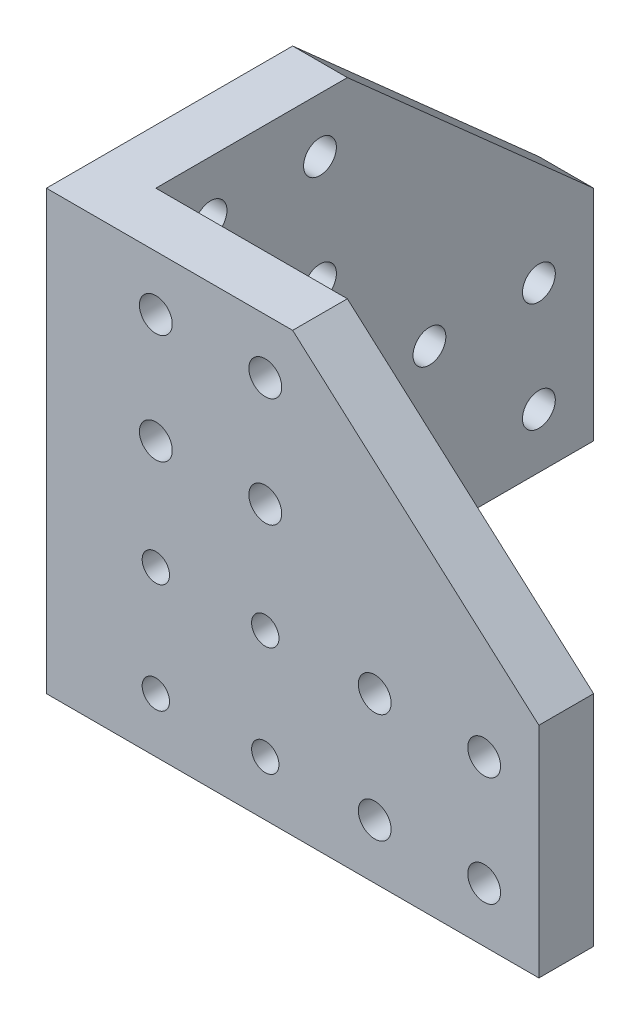
SolidWorks part; units mm, degrees
ref_plane "Front Plane" through (0, 0, 0) normal (0, 0, 1) x (1, 0, 0)
ref_plane "Top Plane" through (0, 0, 0) normal (0, 1, 0) x (1, 0, 0)
ref_plane "Right Plane" through (0, 0, 0) normal (1, 0, 0) x (0, 0, -1)
sketch "Sketch1" plane through (0, 0, 0) normal (0, 1, 0) x (1, 0, 0)
  line L0 (0, 0) -> (90, 0)
  line L1 (90, 0) -> (90, 10)
  line L2 (90, 10) -> (10, 10)
  line L3 (10, 10) -> (10, 90)
  line L4 (10, 90) -> (0, 90)
  line L5 (0, 90) -> (0, 0)
  dimension "D1" = 90
  dimension "D2" = 10
  dimension "D3" = 80
  dimension "D4" = 10
extrude "Boss-Extrude1" add sketch "Sketch1" along normal blind 80
sketch "Sketch2" plane through (0, 0, 0) normal (0, 0, 1) x (1, 0, 0)
  line L0 (90, 80) -> (90, 40)
  line L1 (90, 80) -> (90, 0) construction
  line L2 (90, 40) -> (45, 80)
  line L3 (0, 80) -> (90, 80) construction
  line L4 (45, 80) -> (90, 80)
extrude "Cut-Extrude1" cut sketch "Sketch2" against normal up to next
sketch "Sketch3" plane through (0, 0, 0) normal (-1, 0, 0) x (0, 0, 1)
  line L0 (-45, 80) -> (-90, 40)
  line L1 (-90, 80) -> (0, 80) construction
  line L2 (-90, 80) -> (-90, 0) construction
  line L3 (-90, 40) -> (-90, 80)
  line L4 (-90, 80) -> (-45, 80)
extrude "Cut-Extrude2" cut sketch "Sketch3" against normal up to next
sketch "Sketch4" plane through (0, 0, 0) normal (0, 0, 1) x (1, 0, 0)
  line L0 (0, 80) -> (0, 0) construction
  line L1 (90, 40) -> (90, 0) construction
  line L2 (0, 80) -> (45, 80) construction
  line L3 (0, 0) -> (90, 0) construction
  circle A0 centre (20, 30) radius 2.5
  circle A1 centre (40, 30) radius 2.5
  circle A2 centre (20, 10) radius 2.5
  circle A3 centre (40, 10) radius 2.5
  circle A4 centre (60, 10) radius 3
  circle A5 centre (80, 10) radius 3
  circle A6 centre (60, 30) radius 3
  circle A7 centre (80, 30) radius 3
  circle A8 centre (40, 50) radius 3
  circle A9 centre (20, 50) radius 3
  circle A10 centre (20, 70) radius 3
  circle A11 centre (40, 70) radius 3
  dimension "D8" = 6
  dimension "D9" = 5
  dimension "D1" = 20
  dimension "D2" = 20
  dimension "D3" = 10
  dimension "D4" = 20
  dimension "D5" = 20
  dimension "D6" = 20
  dimension "D7" = 10
  dimension "D10" = 10
extrude "Cut-Extrude3" cut sketch "Sketch4" against normal up to next
sketch "Sketch5" plane through (0, 0, 0) normal (-1, 0, 0) x (0, 0, 1)
  line L0 (0, 80) -> (0, 0) construction
  line L1 (-90, 40) -> (-90, 0) construction
  line L2 (-90, 0) -> (0, 0) construction
  line L3 (-45, 80) -> (0, 80) construction
  circle A0 centre (-20, 70) radius 3
  circle A1 centre (-40, 70) radius 3
  circle A2 centre (-20, 50) radius 3
  circle A3 centre (-40, 50) radius 3
  circle A4 centre (-20, 30) radius 3
  circle A5 centre (-40, 30) radius 3
  circle A6 centre (-20, 10) radius 3
  circle A7 centre (-40, 10) radius 3
  circle A8 centre (-60, 10) radius 3
  circle A9 centre (-60, 30) radius 3
  circle A10 centre (-80, 30) radius 3
  circle A11 centre (-80, 10) radius 3
  dimension "D1" = 6
  dimension "D2" = 20
  dimension "D3" = 20
  dimension "D4" = 10
  dimension "D5" = 20
  dimension "D6" = 10
  dimension "D7" = 20
  dimension "D8" = 20
  dimension "D9" = 10
extrude "Cut-Extrude4" cut sketch "Sketch5" against normal up to next
